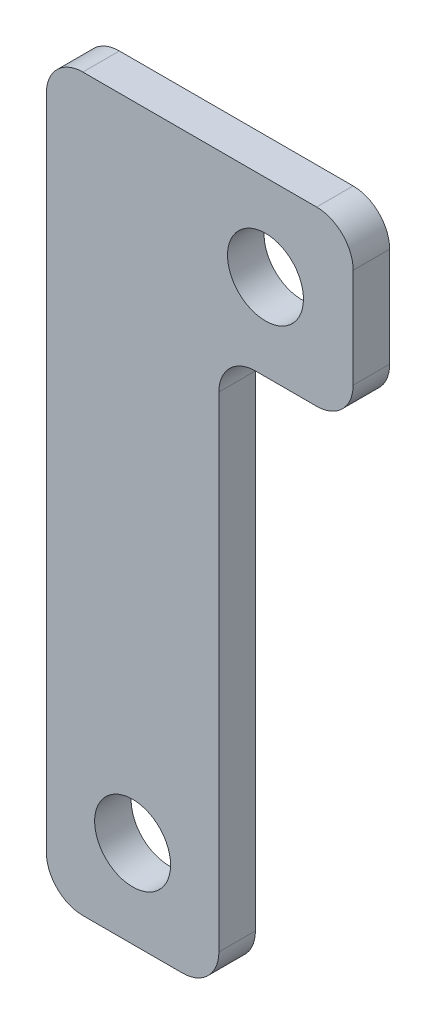
SolidWorks part; units mm, degrees
material "3003-H14"
ref_plane "X-Y Datum" through (0, 0, 0) normal (0, 0, 1) x (1, 0, 0)
ref_plane "X-Z Datum" through (0, 0, 0) normal (0, 1, 0) x (1, 0, 0)
ref_plane "Y-Z Datum" through (0, 0, 0) normal (1, 0, 0) x (0, 0, -1)
sketch "Sketch1" plane through (0, 0, 0) normal (0, 0, 1) x (1, 0, 0)
  line L0 (-141.0159, 133.5285) -> (-141.0159, 118.5285) construction
  line L1 (-141.0159, 133.5285) -> (-133.3959, 133.5285)
  line L2 (-133.3959, 133.5285) -> (-133.3959, 118.5285)
  line L3 (-133.3959, 118.5285) -> (-141.0159, 118.5285)
  line L4 (-141.0159, 133.5285) -> (-160.0659, 133.5285)
  line L5 (-160.0659, 133.5285) -> (-160.0659, 70.0285)
  line L6 (-160.0659, 70.0285) -> (-145.0659, 70.0285)
  line L7 (-145.0659, 70.0285) -> (-145.0659, 118.5285)
  line L8 (-145.0659, 118.5285) -> (-141.0159, 118.5285)
  line L9 (-160.0659, 77.6485) -> (-145.0659, 77.6485) construction
  circle A0 centre (-141.0159, 126.0285) radius 3 construction
  circle A1 centre (-141.0159, 126.0285) radius 3 construction
  circle A2 centre (-152.5659, 77.6485) radius 3 construction
  point P5 (-141.0159, 126.0285)
  dimension "D6" = 6
  dimension "D1" = 15
  dimension "D2" = 15
  dimension "D3" = 7.62
  dimension "D4" = 19.05
  dimension "D5" = 63.5
  dimension "D7" = 7.62
extrude "Boss-Extrude1" add sketch "Sketch1" along normal blind 3.175
hole_wizard "M6 Clearance Hole1" positions "Sketch2" profile "Sketch3" hole size "M6" standard "ANSI Metric" end condition through all
sketch "Sketch2" plane through (0, 0, 3.175) normal (0, 0, 1) x (1, 0, 0)
  point P0 (-141.0159, 126.0285)
  point P3 (-152.5659, 77.6485)
sketch "Sketch3" plane through (-141.0159, 126.0285, 3.175) normal (1, 0, 0) x (0, -1, 0)
  line L0 (0, 0) -> (0, 3.175)
  line L1 (0, 3.175) -> (3.3, 3.175)
  line L2 (3.3, 3.175) -> (3.3, 0)
  line L5 (3.3, 0) -> (0, 0)
  line L11 (0, -6.35) -> (0, 107.95) construction
  dimension "Thru Hole Dia." = 6.6
  dimension "Thru Hole Depth" = 3.175
fillet "Fillet1" radius 3.175 6 edges at (-145.0659, 70.0285, 1.5875) (-160.0659, 70.0285, 1.5875) (-160.0659, 133.5285, 1.5875) (-145.0659, 118.5285, 1.5875) (-133.3959, 118.5285, 1.5875) (-133.3959, 133.5285, 1.5875)
